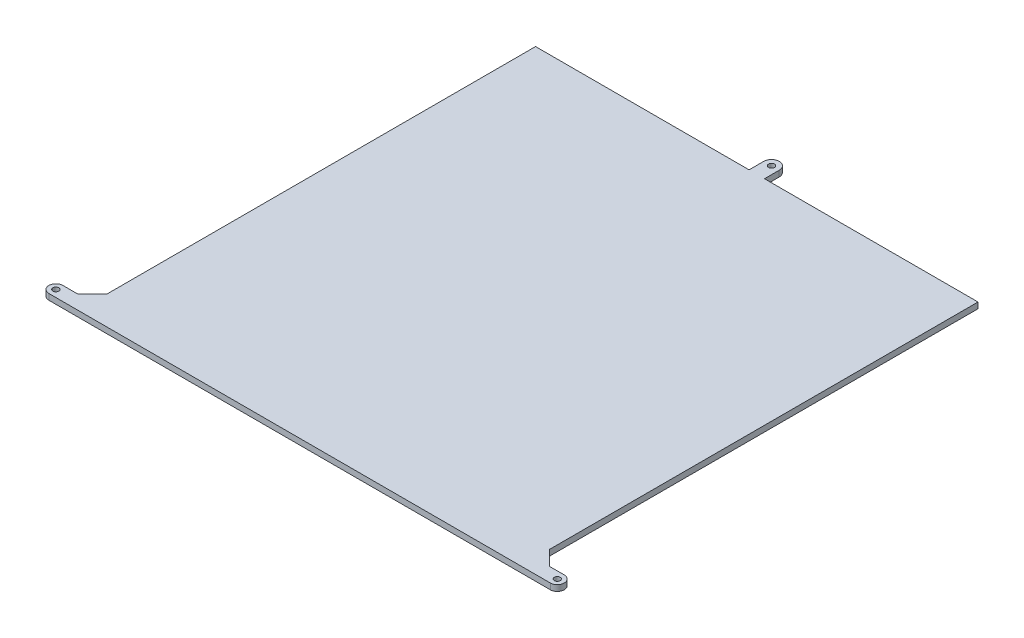
SolidWorks part; units mm, degrees
ref_plane "Front Plane" through (0, 0, 0) normal (0, 0, 1) x (1, 0, 0)
ref_plane "Top Plane" through (0, 0, 0) normal (0, 1, 0) x (1, 0, 0)
ref_plane "Right Plane" through (0, 0, 0) normal (1, 0, 0) x (0, 0, -1)
sketch "Sketch1" plane through (0, 0, 0) normal (0, 1, 0) x (1, 0, 0)
  line L0 (-170, -160) -> (170, -160)
  line L1 (-150, 150) -> (-5.2208, 150)
  line L2 (-150, 150) -> (-150, -140.5272)
  line L3 (-5.2208, 160) -> (-5.2208, 150)
  line L4 (150, 150) -> (150, -140.5272)
  line L5 (-150, 150) -> (150, -150) construction
  line L6 (-150, -150) -> (150, 150) construction
  line L7 (170, -150.5272) -> (160, -150.5272)
  line L8 (-170, -150.5272) -> (-160, -150.5272)
  line L9 (5.2208, 160) -> (5.2208, 150)
  line L10 (5.2208, 150) -> (150, 150)
  line L11 (-160, -150.5272) -> (-150, -140.5272)
  line L12 (160, -150.5272) -> (150, -140.5272)
  circle A0 centre (0, 160) radius 2
  circle A1 centre (-170, -155.2636) radius 2
  circle A2 centre (170, -155.2636) radius 2
  arc A3 (-170, -150.5272) -> (-170, -160) centre (-170, -155.2636) ccw
  arc A4 (170, -160) -> (170, -150.5272) centre (170, -155.2636) ccw
  arc A5 (-5.2208, 160) -> (5.2208, 160) centre (0, 160) cw
  point P0 (0, 0)
  point P10 (0, 0)
  point P18 (-150, -150.5272)
  point P20 (150, -150.5272)
  point P27 (0, 0)
  dimension "D2" = 4
  dimension "D3" = 4
  dimension "D6" = 4
  dimension "D1" = 300
  dimension "D4" = 10
  dimension "D7" = 10
extrude "Boss-Extrude1" add sketch "Sketch1" along normal blind 4 contours A5 L3 L1 L2 L11 L8 A3 L0 A4 A2 L7 L12 L4 L10 L9 A1 A0
